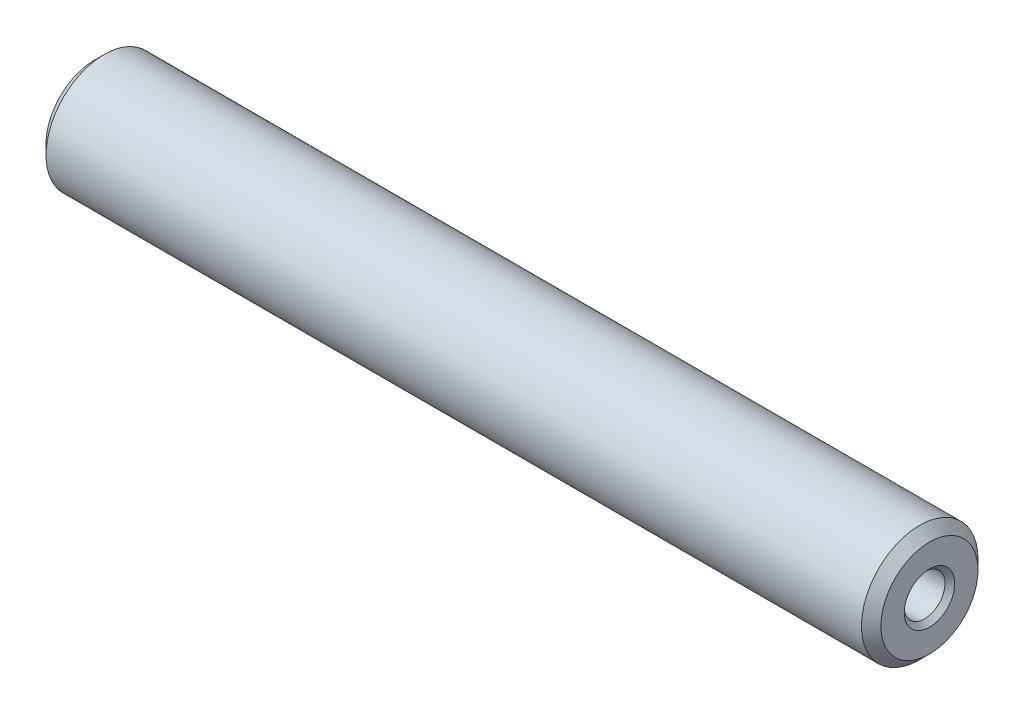
SolidWorks part; units mm, degrees
material "Chrome Stainless Steel"
ref_plane "Front Plane" through (0, 0, 0) normal (0, 0, 1) x (1, 0, 0)
ref_plane "Top Plane" through (0, 0, 0) normal (0, 1, 0) x (1, 0, 0)
ref_plane "Right Plane" through (0, 0, 0) normal (1, 0, 0) x (0, 0, -1)
sketch "Sketch1" plane through (0, 0, 0) normal (1, 0, 0) x (0, 0, -1)
  circle A0 centre (0, 0) radius 6
  dimension "D1" = 12
extrude "Boss-Extrude1" add sketch "Sketch1" along normal blind 86
chamfer "Chamfer1" distance 1 angle 45 2 edges at (86, 0, -6) (0, 0, -6)
hole_wizard "M5 Tapped Hole1" positions "Sketch3" profile "Sketch2" tap size "M5" standard "ISO"
sketch "Sketch3" plane through (86, 0, 0) normal (1, 0, 0) x (0, 0, -1)
  point P1 (0, 0)
sketch "Sketch2" plane through (86, 0, 0) normal (0, 1, 0) x (0, 0, -1)
  line L0 (0, 0) -> (0, 15.2618)
  line L1 (0, 15.2618) -> (2.1, 14)
  line L2 (2.1, 14) -> (2.1, 0)
  line L5 (2.1, 0) -> (0, 0)
  line L10 (0, 15.2618) -> (-2.1, 14) construction
  line L11 (0, -6.35) -> (0, 107.95) construction
  dimension "Tap Drill Dia." = 4.2
  dimension "Tap Drill Depth" = 14
  dimension "Drill Angle" = 118
cosmetic thread "Hole Thread1" parameters "D1"=10, "D2"=5
chamfer "Chamfer2" distance 0.5 angle 45 1 edges at (86, 0, -2.1)
hole_wizard "M5 Tapped Hole2" positions "Sketch5" profile "Sketch4" tap size "M5" standard "ISO"
sketch "Sketch5" plane through (0, 0, 0) normal (-1, 0, 0) x (0, 0, 1)
  point P1 (0, 0)
sketch "Sketch4" plane through (0, 0, 0) normal (0, 1, 0) x (0, 0, 1)
  line L0 (0, 0) -> (0, 15.2618)
  line L1 (0, 15.2618) -> (2.1, 14)
  line L2 (2.1, 14) -> (2.1, 0)
  line L5 (2.1, 0) -> (0, 0)
  line L10 (0, 15.2618) -> (-2.1, 14) construction
  line L11 (0, -6.35) -> (0, 107.95) construction
  dimension "Tap Drill Dia." = 4.2
  dimension "Tap Drill Depth" = 14
  dimension "Drill Angle" = 118
cosmetic thread "Hole Thread2" parameters "D1"=10, "D2"=5
chamfer "Chamfer3" distance 0.5 angle 45 1 edges at (0, 0, 2.1)
